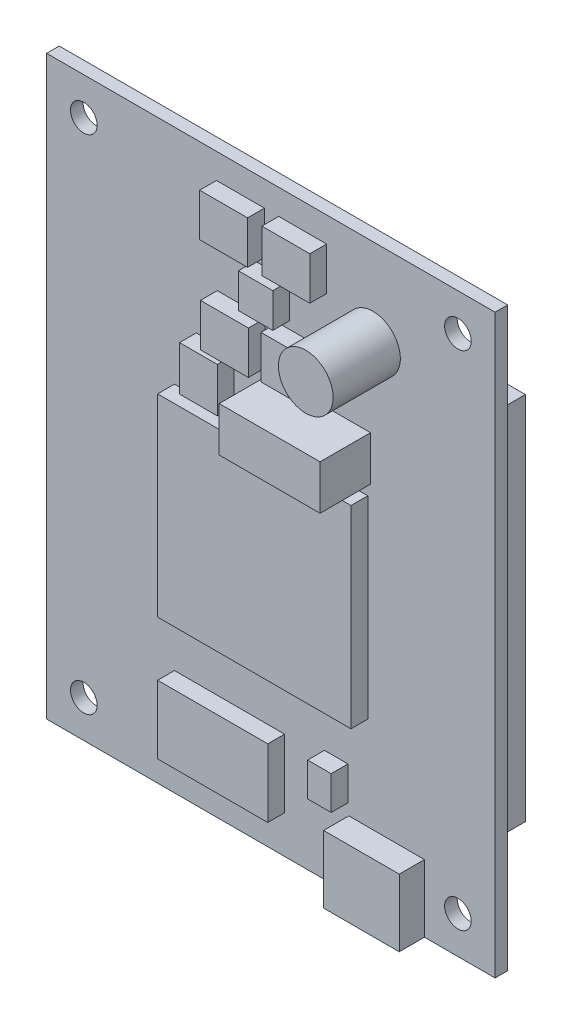
SolidWorks part; units mm, degrees
ref_plane "前视基准面" through (0, 0, 0) normal (0, 0, 1) x (1, 0, 0)
ref_plane "上视基准面" through (0, 0, 0) normal (0, 1, 0) x (1, 0, 0)
ref_plane "右视基准面" through (0, 0, 0) normal (1, 0, 0) x (0, 0, -1)
sketch "草图1" plane through (0, 0, 0) normal (0, 0, 1) x (1, 0, 0)
  line L0 (0, 4.42) -> (53.34, 4.42) construction
  line L1 (0, 0) -> (53.34, 0)
  line L2 (0, 0) -> (0, 68.58)
  line L3 (0, 68.58) -> (53.34, 68.58)
  line L4 (53.34, 0) -> (53.34, 68.58)
  line L5 (0, 64.16) -> (53.34, 64.16) construction
  line L6 (4.42, 68.58) -> (4.42, 0) construction
  line L7 (48.92, 68.58) -> (48.92, 0) construction
  circle A0 centre (48.92, 64.16) radius 1.585
  circle A1 centre (4.42, 64.16) radius 1.585
  circle A2 centre (4.42, 4.42) radius 1.585
  circle A3 centre (48.92, 4.42) radius 1.585
  dimension "D7" = 3.17
  dimension "D8" = 3.17
  dimension "D9" = 3.17
  dimension "D10" = 3.17
  dimension "D1" = 68.58
  dimension "D2" = 53.34
  dimension "D3" = 4.42
  dimension "D4" = 4.42
  dimension "D5" = 4.42
  dimension "D6" = 4.42
extrude "凸台-拉伸1" add sketch "草图1" along normal blind 1.5
sketch "草图2" plane through (0, 0, 1.5) normal (0, 0, 1) x (1, 0, 0)
  circle A0 centre (38.82, 58.16) radius 3.25
  circle A2 centre (48.92, 64.16) radius 1.585 construction
  dimension "D3" = 6.5
  dimension "D1" = 10.1
  dimension "D2" = 6
extrude "凸台-拉伸2" add sketch "草图2" along normal blind 8
sketch "草图3" plane through (0, 0, 1.5) normal (0, 0, 1) x (1, 0, 0)
  line L1 (38.52, 48.76) -> (26.52, 48.76)
  line L2 (38.52, 48.76) -> (38.52, 43.46)
  line L3 (38.52, 43.46) -> (26.52, 43.46)
  line L4 (26.52, 48.76) -> (26.52, 43.46)
  circle A0 centre (48.92, 64.16) radius 1.585 construction
  dimension "D1" = 10.4
  dimension "D2" = 15.4
  dimension "D3" = 12
  dimension "D4" = 5.3
extrude "凸台-拉伸3" add sketch "草图3" along normal blind 6
sketch "草图4" plane through (0, 0, 1.5) normal (0, 0, 1) x (1, 0, 0)
  line L0 (53.34, 0) -> (53.34, 68.58) construction
  line L1 (33.04, 13.3) -> (35.84, 13.3)
  line L2 (33.04, 13.3) -> (33.04, 9.3)
  line L3 (33.04, 9.3) -> (35.84, 9.3)
  line L4 (35.84, 13.3) -> (35.84, 9.3)
  line L5 (0, 0) -> (53.34, 0) construction
  dimension "D1" = 17.5
  dimension "D2" = 9.3
  dimension "D3" = 4
  dimension "D4" = 2.8
extrude "凸台-拉伸4" add sketch "草图4" along normal blind 2
sketch "草图5" plane through (0, 0, 0) normal (0, 0, -1) x (-1, 0, 0)
  line L0 (-53.34, 0) -> (-53.34, 68.58) construction
  line L1 (-46.64, 56.4) -> (-51.44, 56.4)
  line L2 (-46.64, 56.4) -> (-46.64, 12.4)
  line L3 (-46.64, 12.4) -> (-51.44, 12.4)
  line L4 (-51.44, 56.4) -> (-51.44, 12.4)
  line L5 (-1.9, 56.4) -> (-6.7, 56.4)
  line L6 (-1.9, 56.4) -> (-1.9, 12.4)
  line L7 (-1.9, 12.4) -> (-6.7, 12.4)
  line L8 (-6.7, 56.4) -> (-6.7, 12.4)
  line L9 (0, 0) -> (-53.34, 0) construction
  line L10 (0, 68.58) -> (0, 0) construction
  dimension "D1" = 4.8
  dimension "D2" = 4.8
  dimension "D3" = 44
  dimension "44" = 44
  dimension "D4" = 1.9
  dimension "D5" = 12.4
  dimension "D6" = 12.4
  dimension "D7" = 1.9
extrude "凸台-拉伸5" add sketch "草图5" along normal blind 4
sketch "草图6" plane through (0, 0, 1.5) normal (0, 0, 1) x (1, 0, 0)
  line L0 (0, 0) -> (53.34, 0) construction
  line L1 (35.94, 0) -> (44.94, 0)
  line L2 (35.94, 0) -> (35.94, 8)
  line L3 (35.94, 8) -> (44.94, 8)
  line L4 (44.94, 0) -> (44.94, 8)
  line L5 (53.34, 0) -> (53.34, 68.58) construction
  dimension "D1" = 8.4
  dimension "D2" = 8
  dimension "D3" = 9
extrude "凸台-拉伸6" add sketch "草图6" along normal blind 3
sketch "草图7" plane through (0, 0, 1.5) normal (0, 0, 1) x (1, 0, 0)
  line L0 (0, 68.58) -> (0, 0) construction
  line L1 (15.2, 12.6) -> (28.3, 12.6)
  line L2 (15.2, 12.6) -> (15.2, 4.5)
  line L3 (15.2, 4.5) -> (28.3, 4.5)
  line L4 (28.3, 12.6) -> (28.3, 4.5)
  line L5 (0, 0) -> (35.94, 0) construction
  line L6 (53.34, 68.58) -> (0, 68.58) construction
  line L7 (17.8, 48.68) -> (22.3, 48.68)
  line L8 (17.8, 48.68) -> (17.8, 43.38)
  line L9 (17.8, 43.38) -> (22.3, 43.38)
  line L10 (22.3, 48.68) -> (22.3, 43.38)
  line L12 (20.2, 65.58) -> (25.9, 65.58)
  line L13 (20.2, 65.58) -> (20.2, 60.48)
  line L14 (20.2, 60.48) -> (25.9, 60.48)
  line L15 (25.9, 65.58) -> (25.9, 60.48)
  line L16 (27.6, 65.58) -> (33.3, 65.58)
  line L17 (27.6, 65.58) -> (27.6, 60.48)
  line L18 (27.6, 60.48) -> (33.3, 60.48)
  line L19 (33.3, 65.58) -> (33.3, 60.48)
  line L20 (20.3, 54.28) -> (26, 54.28)
  line L21 (20.3, 54.28) -> (20.3, 49.18)
  line L22 (20.3, 49.18) -> (26, 49.18)
  line L23 (26, 54.28) -> (26, 49.18)
  line L24 (27.5, 54.58) -> (33.2, 54.58)
  line L25 (27.5, 54.58) -> (27.5, 49.48)
  line L26 (27.5, 49.48) -> (33.2, 49.48)
  line L27 (33.2, 54.58) -> (33.2, 49.48)
  line L28 (24.8, 59.58) -> (28.9, 59.58)
  line L29 (24.8, 59.58) -> (24.8, 55.48)
  line L30 (24.8, 55.48) -> (28.9, 55.48)
  line L31 (28.9, 59.58) -> (28.9, 55.48)
  line L32 (15.2, 19.1) -> (38.2, 19.1)
  line L33 (15.2, 19.1) -> (15.2, 42.1)
  line L34 (15.2, 42.1) -> (38.2, 42.1)
  line L35 (38.2, 19.1) -> (38.2, 42.1)
  dimension "D1" = 15.2
  dimension "D2" = 4.5
  dimension "D3" = 13.1
  dimension "D4" = 8.1
  dimension "D5" = 17.8
  dimension "D6" = 19.9
  dimension "D7" = 4.5
  dimension "D8" = 5.3
  dimension "D9" = 20.2
  dimension "D10" = 3
  dimension "D11" = 5.7
  dimension "D12" = 5.1
  dimension "D13" = 5.7
  dimension "D14" = 5.1
  dimension "D15" = 5.7
  dimension "D16" = 5.1
  dimension "D17" = 5.7
  dimension "D18" = 5.1
  dimension "D19" = 1.7
  dimension "D20" = 0.1
  dimension "D21" = 6.2
  dimension "D22" = 1.5
  dimension "D23" = 0.3
  dimension "D24" = 4.6
  dimension "D25" = 0.9
  dimension "D26" = 4.1
  dimension "D27" = 4.1
  dimension "D28" = 15.2
  dimension "D29" = 19.1
  dimension "D30" = 23
  dimension "D31" = 23
extrude "凸台-拉伸7" add sketch "草图7" along normal blind 2
